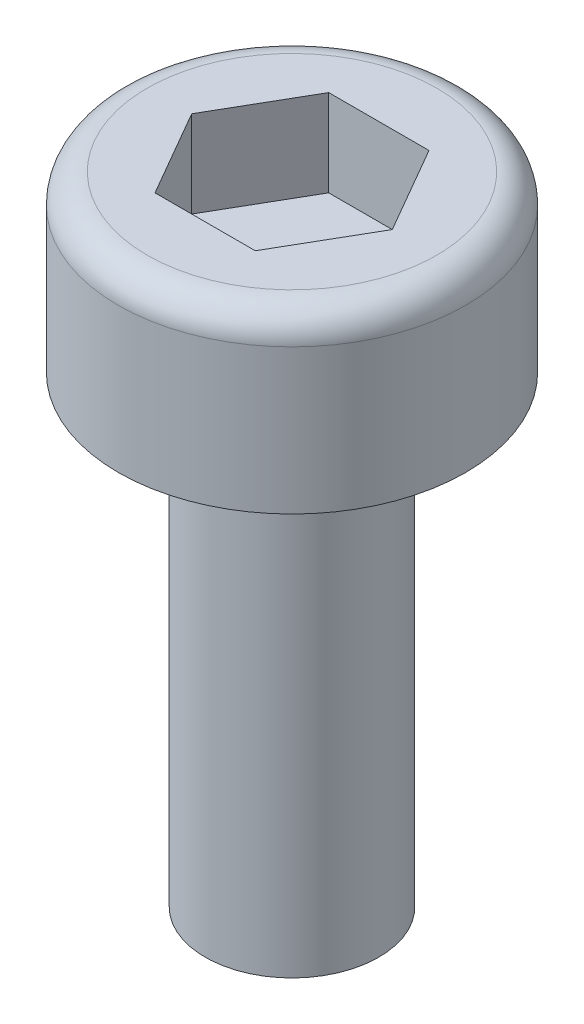
SolidWorks part; units mm, degrees
material "Plain Carbon Steel"
ref_plane "Front Plane" through (0, 0, 0) normal (0, 0, 1) x (1, 0, 0)
ref_plane "Top Plane" through (0, 0, 0) normal (0, 1, 0) x (1, 0, 0)
ref_plane "Right Plane" through (0, 0, 0) normal (1, 0, 0) x (0, 0, -1)
sketch "Sketch1" plane through (0, 0, 0) normal (0, 0, 1) x (1, 0, 0)
  line L0 (0, 0) -> (0, 36.502) construction
  line L1 (0, 0) -> (3, 0)
  line L2 (3, 0) -> (3, 16)
  line L3 (3, 16) -> (6, 16)
  line L4 (6, 16) -> (6, 22)
  line L5 (6, 22) -> (0, 22)
  line L6 (0, 0) -> (0, 22)
  dimension "D1" = 6
  dimension "D2" = 16
  dimension "D3" = 6
  dimension "D4" = 12
revolve "Revolve1" add sketch "Sketch1" angle 360 about L0
sketch "Sketch2" plane through (0, 22, 0) normal (0, 1, 0) x (1, 0, 0)
  line L1 (1.7321, 3) -> (-1.7321, 3)
  line L2 (-1.7321, 3) -> (-3.4641, 0)
  line L3 (-3.4641, 0) -> (-1.7321, -3)
  line L4 (-1.7321, -3) -> (1.7321, -3)
  line L5 (1.7321, -3) -> (3.4641, 0)
  line L6 (3.4641, 0) -> (1.7321, 3)
  circle A0 centre (0, 0) radius 3 construction
  dimension "D1" = 6
extrude "Cut-Extrude1" cut sketch "Sketch2" against normal blind 3
fillet "Fillet1" radius 1 1 edges at (0, 22, -6)
